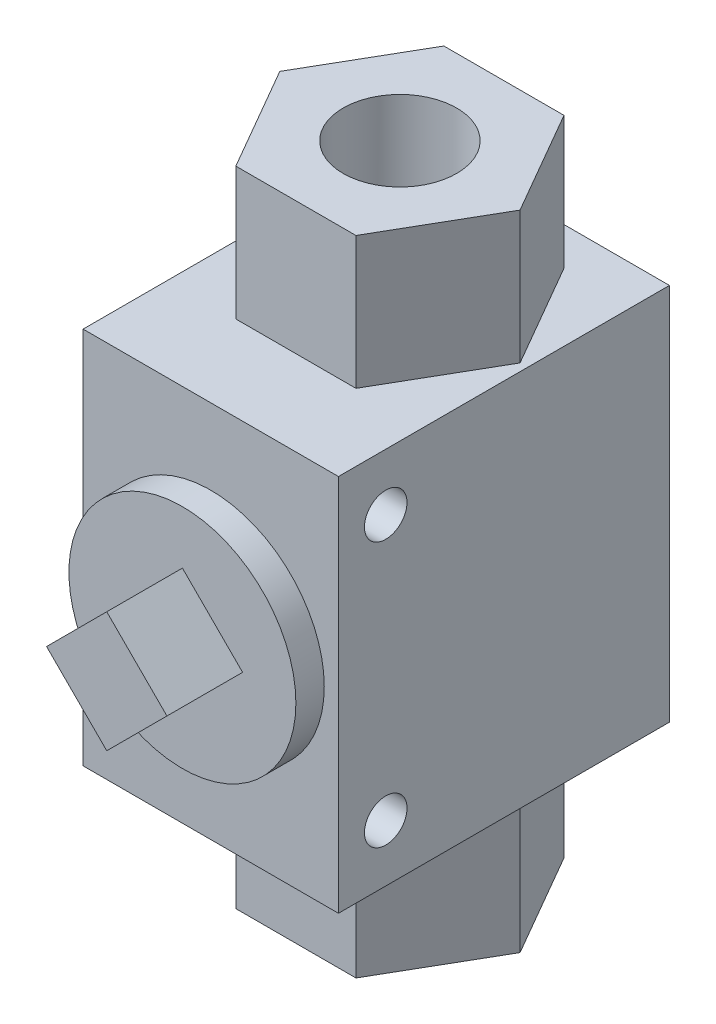
SolidWorks part; units mm, degrees
ref_plane "Front Plane" through (0, 0, 0) normal (1, 0, 0) x (0, 1, 0)
ref_plane "Top Plane" through (0, 0, 0) normal (0, 0, 1) x (0, 1, 0)
ref_plane "Right Plane" through (0, 0, 0) normal (0, 1, 0) x (-1, 0, 0)
sketch "Sketch1" plane through (0, 0, 0) normal (1, 0, 0) x (0, 1, 0)
  line L1 (-20, -17.5) -> (20, -17.5)
  line L2 (-20, -17.5) -> (-20, 17.5)
  line L3 (-20, 17.5) -> (20, 17.5)
  line L4 (20, -17.5) -> (20, 17.5)
  line L5 (-20, -17.5) -> (20, 17.5) construction
  line L6 (-20, 17.5) -> (20, -17.5) construction
  circle A0 centre (-14, 12.5) radius 2.25
  circle A1 centre (14, 12.5) radius 2.25
  point P0 (0, 0)
  dimension "D3" = 4.5
  dimension "D1" = 40
  dimension "D2" = 35
  dimension "D4" = 6
  dimension "D6" = 5
  dimension "D5" = 2
extrude "Boss-Extrude1" add sketch "Sketch1" along normal blind 27
sketch "Sketch2" plane through (0, 20, 0) normal (0, 1, 0) x (-1, 0, 0)
  line L0 (-13.5, 17.5) -> (-13.5, -17.5) construction
  line L1 (-27, 17.5) -> (0, 17.5) construction
  line L2 (-27, -17.5) -> (0, -17.5) construction
  line L4 (-0.7983, -2.5) -> (-7.1491, 8.5)
  line L5 (-7.1491, 8.5) -> (-19.8509, 8.5)
  line L6 (-19.8509, 8.5) -> (-26.2017, -2.5)
  line L7 (-26.2017, -2.5) -> (-19.8509, -13.5)
  line L8 (-19.8509, -13.5) -> (-7.1491, -13.5)
  line L9 (-7.1491, -13.5) -> (-0.7983, -2.5)
  circle A0 centre (-13.5, -2.5) radius 11 construction
  circle A1 centre (-13.5, -2.5) radius 6
  dimension "D1" = 22
  dimension "D3" = 12
  dimension "D2" = 15
extrude "Boss-Extrude2" add sketch "Sketch2" along normal blind 14 and the other way blind 54
sketch "Sketch3" plane through (0, 0, 17.5) normal (0, 0, 1) x (1, 0, 0)
  line L0 (0, 20) -> (0, -20) construction
  circle A0 centre (13.5, 0) radius 12
  dimension "D1" = 24
  dimension "D2" = 13.5
extrude "Boss-Extrude3" add sketch "Sketch3" along normal blind 3
sketch "Sketch4" plane through (0, 0, 20.5) normal (0, 0, 1) x (1, 0, 0)
  line L1 (13.5, 6.364) -> (7.136, 0)
  line L2 (7.136, 0) -> (13.5, -6.364)
  line L3 (13.5, -6.364) -> (19.864, 0)
  line L4 (19.864, 0) -> (13.5, 6.364)
  circle A0 centre (13.5, 0) radius 4.5 construction
  dimension "D1" = 9
extrude "Boss-Extrude4" add sketch "Sketch4" along normal blind 8
